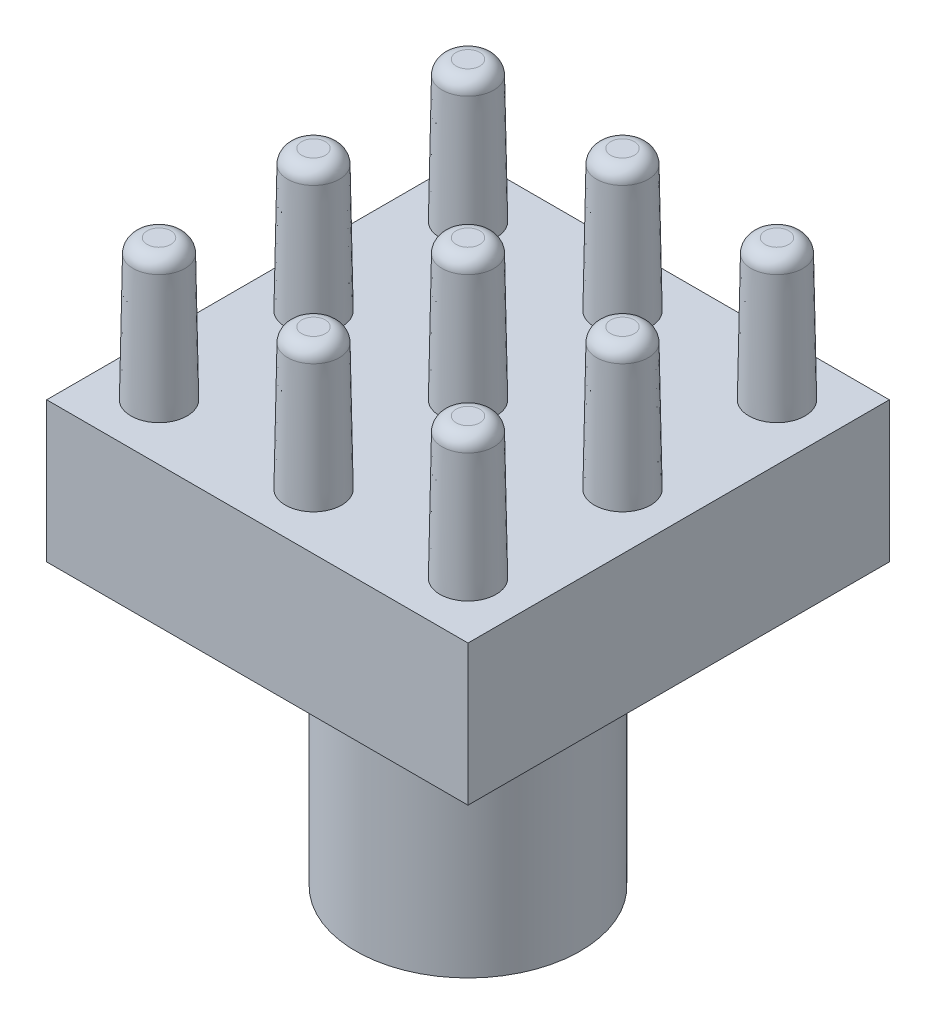
SolidWorks part; units mm, degrees
ref_plane "Front Plane" through (0, 0, 0) normal (0, 0, 1) x (1, 0, 0)
ref_plane "Top Plane" through (0, 0, 0) normal (0, 1, 0) x (1, 0, 0)
ref_plane "Right Plane" through (0, 0, 0) normal (1, 0, 0) x (0, 0, -1)
sketch "Sketch1" plane through (0, 0, 0) normal (0, 1, 0) x (1, 0, 0)
  line L1 (7.5, -7.5) -> (-7.5, -7.5)
  line L2 (7.5, -7.5) -> (7.5, 7.5)
  line L3 (7.5, 7.5) -> (-7.5, 7.5)
  line L4 (-7.5, -7.5) -> (-7.5, 7.5)
  line L5 (7.5, -7.5) -> (-7.5, 7.5) construction
  line L6 (7.5, 7.5) -> (-7.5, -7.5) construction
  point P0 (0, 0)
  dimension "D1" = 15
  dimension "D2" = 15
extrude "Boss-Extrude1" add sketch "Sketch1" along normal blind 5
sketch "Sketch2" plane through (0, 5, 0) normal (0, 1, 0) x (1, 0, 0)
  line L0 (0, 5.5) -> (0, -5.5) construction
  line L1 (5.5, -5.5) -> (-5.5, -5.5) construction
  line L2 (5.5, -5.5) -> (5.5, 5.5) construction
  line L3 (5.5, 5.5) -> (-5.5, 5.5) construction
  line L4 (-5.5, -5.5) -> (-5.5, 5.5) construction
  line L5 (5.5, -5.5) -> (-5.5, 5.5) construction
  line L6 (5.5, 5.5) -> (-5.5, -5.5) construction
  line L7 (-5.5, 0) -> (5.5, 0) construction
  circle A0 centre (-5.5, 5.5) radius 1
  circle A1 centre (0, 5.5) radius 1
  circle A2 centre (5.5, 5.5) radius 1
  circle A3 centre (0, 0) radius 1
  circle A4 centre (-5.5, -5.5) radius 1
  circle A5 centre (0, -5.5) radius 1
  circle A6 centre (5.5, -5.5) radius 1
  circle A7 centre (-5.5, 0) radius 1
  circle A8 centre (5.5, 0) radius 1
  point P0 (0, 0)
  dimension "D3" = 2
  dimension "D4" = 2
  dimension "D5" = 2
  dimension "D6" = 2
  dimension "D7" = 2
  dimension "D8" = 2
  dimension "D9" = 2
  dimension "D10" = 2
  dimension "D11" = 2
  dimension "D1" = 11
  dimension "D2" = 11
extrude "Boss-Extrude2" add sketch "Sketch2" along normal blind 5 draft 1
fillet "Fillet4" radius 0.5 9 edges at (5.5, 10, 6.4127) (5.5, 10, 0.9127) (5.5, 10, -4.5873) (0, 10, -4.5873) (0, 10, 0.9127) (-5.5, 10, -4.5873) (-5.5, 10, 0.9127) (-5.5, 10, 6.4127) (0, 10, 6.4127)
sketch "Sketch3" plane through (0, 0, 0) normal (0, -1, 0) x (1, 0, 0)
  circle A0 centre (0, 0) radius 4
  dimension "D1" = 8
extrude "Boss-Extrude3" add sketch "Sketch3" along normal blind 10
equation "\"base_side\"= 15mm"
equation "\"base_thickness\"= 5mm"
equation "\"Indenter_dia\"= 2mm"
equation "\"Connector_height\"= 10mm"
equation "\"Connector_dia\"= 8mm"
equation "\"Draft_angle\"= 1deg"
equation "\"D3@Boss-Extrude2\"=\"Draft_angle\""
equation "\"D11@Sketch2\"=\"Indenter_dia\""
equation "\"D10@Sketch2\"=\"Indenter_dia\""
equation "\"D5@Sketch2\"=\"Indenter_dia\""
equation "\"D4@Sketch2\"=\"Indenter_dia\""
equation "\"D6@Sketch2\"=\"Indenter_dia\""
equation "\"D9@Sketch2\"=\"Indenter_dia\""
equation "\"D8@Sketch2\"=\"Indenter_dia\""
equation "\"D7@Sketch2\"=\"Indenter_dia\""
equation "\"D3@Sketch2\"=\"Indenter_dia\""
equation "\"D1@Sketch3\"=\"Connector_dia\""
equation "\"D1@Boss-Extrude1\"=\"base_thickness\""
equation "\"D1@Sketch1\"=\"base_side\""
equation "\"D2@Sketch1\"=\"base_side\""
equation "\"D1@Boss-Extrude3\"=\"Connector_height\""
